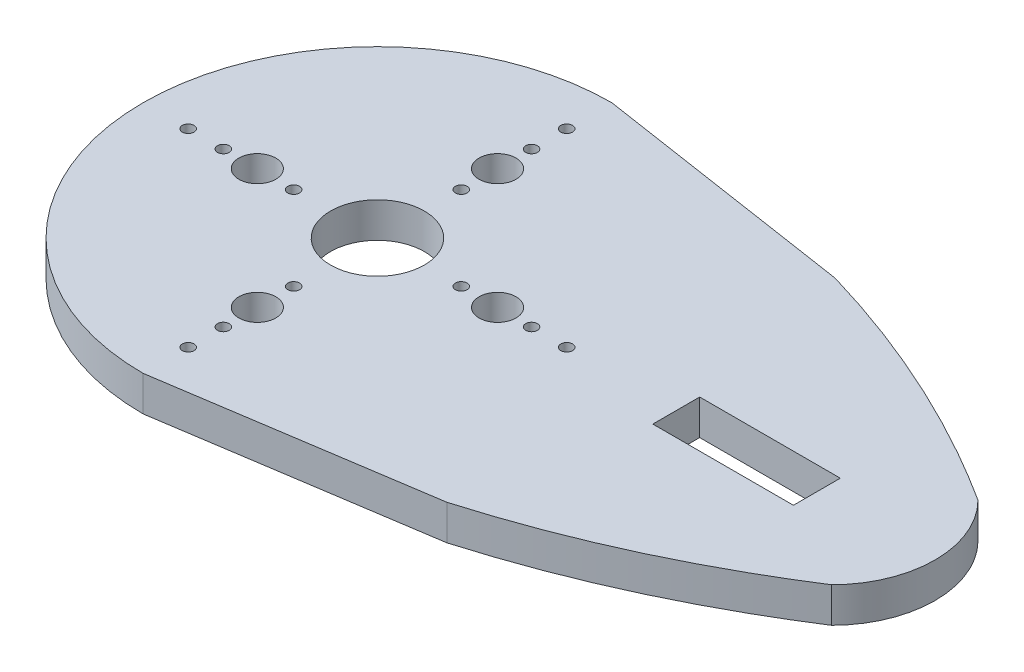
SolidWorks part; units mm, degrees
ref_plane "Front Plane" through (0, 0, 0) normal (0, 0, 1) x (1, 0, 0)
ref_plane "Top Plane" through (0, 0, 0) normal (0, 1, 0) x (1, 0, 0)
ref_plane "Right Plane" through (0, 0, 0) normal (1, 0, 0) x (0, 0, -1)
sketch "Sketch1" plane through (0, 0, 0) normal (0, 1, 0) x (1, 0, 0)
  line L0 (0, -20) -> (0, 20)
  line L1 (0, 20) -> (45, 20)
  line L2 (45, 6.25) -> (45, -6.25)
  line L3 (0, 0) -> (45, 0)
  line L4 (45, 6.25) -> (45, 20)
  line L5 (0, 20) -> (45, 13.125)
  line L6 (45, -6.25) -> (45, -20)
  line L7 (0, -20) -> (45, -13.125)
  line L8 (45, -3.8383) -> (31.5, -3.8383)
  line L9 (0, 0) -> (-7.15, 0)
  line L10 (25.5, 2) -> (37.5, 2)
  line L11 (25.5, 2) -> (25.5, -2)
  line L12 (25.5, -2) -> (37.5, -2)
  line L13 (37.5, 2) -> (37.5, -2)
  line L14 (25.5, 2) -> (37.5, -2) construction
  line L15 (25.5, -2) -> (37.5, 2) construction
  line L16 (-7.15, 0) -> (-10.15, 0)
  line L17 (-10.15, 0) -> (-13.15, 0)
  line L18 (-13.15, 0) -> (-16.15, 0)
  line L19 (0, 10.15) -> (0, 13.15)
  line L20 (0, 13.15) -> (0, 16.15)
  line L21 (0, 7.15) -> (0, 10.15)
  line L22 (0, 0) -> (0, 7.15)
  line L23 (10.15, 0) -> (13.15, 0)
  line L24 (13.15, 0) -> (16.15, 0)
  line L25 (7.15, 0) -> (10.15, 0)
  line L26 (0, 0) -> (7.15, 0)
  line L27 (0, -10.15) -> (0, -13.15)
  line L28 (0, -13.15) -> (0, -16.15)
  line L29 (0, -7.15) -> (0, -10.15)
  line L30 (0, 0) -> (0, -7.15)
  line L31 (0, 2.4291) -> (10.25, 2.4291)
  arc A0 (0, 20) -> (0, -20) centre (0, 0) ccw
  arc A1 (45, 6.25) -> (45, -6.25) centre (38.75, 0) cw
  circle A5 centre (-16.15, 0) radius 0.5
  circle A6 centre (-13.15, 0) radius 0.5
  circle A7 centre (-10.15, 0) radius 0.5
  circle A8 centre (-7.15, 0) radius 0.5
  circle A9 centre (0, 0) radius 4
  circle A10 centre (0, 10.15) radius 0.5
  circle A11 centre (0, 13.15) radius 0.5
  circle A12 centre (0, 16.15) radius 0.5
  circle A13 centre (0, 7.15) radius 0.5
  circle A14 centre (10.15, 0) radius 0.5
  circle A15 centre (13.15, 0) radius 0.5
  circle A16 centre (16.15, 0) radius 0.5
  circle A17 centre (7.15, 0) radius 0.5
  circle A18 centre (0, -10.15) radius 0.5
  circle A19 centre (0, -13.15) radius 0.5
  circle A20 centre (0, -16.15) radius 0.5
  circle A21 centre (0, -7.15) radius 0.5
  circle A22 centre (10.25, 0) radius 1.575
  circle A23 centre (0, -10.25) radius 1.575
  circle A24 centre (-10.25, 0) radius 1.575
  circle A25 centre (0, 10.25) radius 1.575
  spline S0 degree 2 poles (0, 20) (24.3878, 19.4353) (45, 6.25) knots 0 0 0 1 1 1
  spline S1 degree 2 poles (0, -20) (24.3878, -19.4353) (45, -6.25) knots 0 0 0 1 1 1
  point P16 (31.5, 0)
  point P57 (0, 0)
  point P68 (0, 0)
  dimension "D10" = 8
  dimension "D8" = 1
  dimension "D13" = 3.15
  dimension "D1" = 40
  dimension "D2" = 45
  dimension "D3" = 12.5
  dimension "D4" = 13.5
  dimension "D5" = 12
  dimension "D6" = 4
  dimension "D7" = 3
  dimension "D9" = 7.15
  dimension "D12" = 10.25
  dimension "D11" = 4
  dimension "D14" = 4
extrude "Boss-Extrude1" add sketch "Sketch1" along normal blind 3
